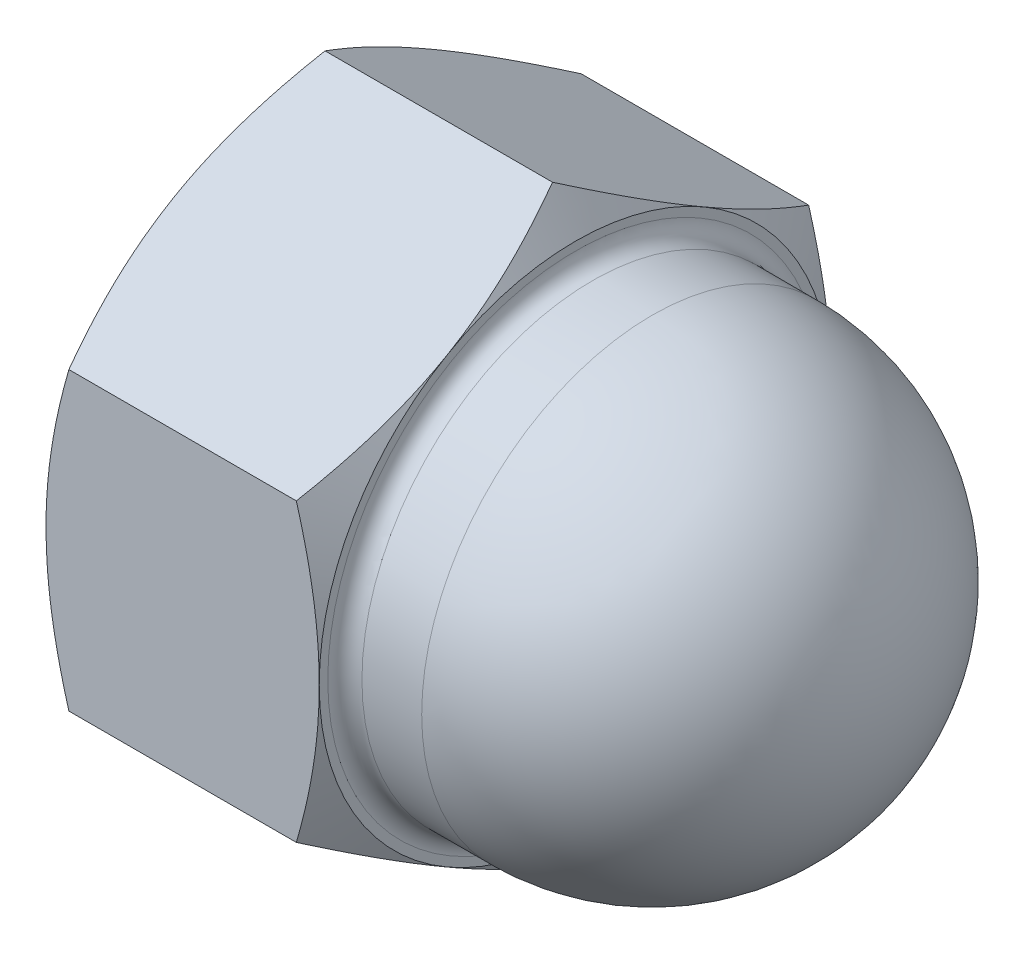
SolidWorks part; units mm, degrees
extrude "BaseNut" add sketch "BaseNutSke" along normal blind 16
sketch "BaseNutSke" plane through (0, 0, 0) normal (1, 0, 0) x (0, 0, -1)
  line L6 (15, 8.6603) -> (15, -8.6603)
  line L7 (-15, 8.6603) -> (-15, -8.6603)
  line L8 (15, 8.6603) -> (0, 17.3205)
  line L9 (0, 17.3205) -> (-15, 8.6603)
  line L10 (-15, -8.6603) -> (0, -17.3205)
  line L11 (0, -17.3205) -> (15, -8.6603)
  dimension "D4" = 60
  dimension "D1" = 120
  dimension "D2" = 15
  dimension "D3" = 15
  dimension "Width_flats" = 30
revolve "DoubleChamfer" cut sketch "Sketch4" angle 360 about L10
sketch "Sketch4" plane through (0, 0, 0) normal (0, 0, 1) x (1, 0, 0)
  line L0 (0, 15) -> (2.7831, 19.8205)
  line L1 (16, 15) -> (13.2169, 19.8205)
  line L2 (2.7831, 19.8205) -> (13.2169, 19.8205)
  line L3 (16, 15) -> (18, 15)
  line L4 (18, 15) -> (18, 30)
  line L5 (18, 30) -> (-2, 30)
  line L6 (0, 15) -> (-2, 15)
  line L7 (-2, 15) -> (-2, 30)
  line L8 (16, 17.3205) -> (16, 8.6603) construction
  line L9 (0, 17.3205) -> (0, 8.6603) construction
  line L10 (0, 0) -> (57.15, 0) construction
  line L11 (16, 17.3205) -> (0, 17.3205) construction
  point P17 (16, 15)
  dimension "D1" = 30
  dimension "D2" = 30
  dimension "D3" = 2
  dimension "D4" = 2
  dimension "D5" = 2.5
  dimension "D6" = 15
  dimension "D7" = 15
revolve "TapDrill" cut sketch "TapDriSke"
sketch "TapDriSke" plane through (0, 0, 0) normal (0, 0, 1) x (1, 0, 0)
  line L0 (0, 0) -> (44.45, 0) construction
  line L1 (0, 8.75) -> (27, 8.75)
  line L2 (0, 12.9904) -> (0, 0) construction
  line L3 (27, 8.75) -> (32.2575, 0)
  line L4 (0, 0) -> (63.5, 0) construction
  line L5 (32.2575, 0) -> (0, 0)
  line L6 (0, 0) -> (0, 8.75)
  line L7 (27, -8.75) -> (32.2575, 0) construction
  line L8 (0, -8.75) -> (27, -8.75) construction
  line L9 (0.5, 6.35) -> (0.5, 3.175) construction
  dimension "Drill_depth" = 27
cosmetic thread "ThreadCosmetic" [suppressed]
revolve "EndChamfer" cut sketch "EndChamferSketch" angle 360 about L4
sketch "EndChamferSketch" plane through (0, 0, 0) normal (0, 0, 1) x (1, 0, 0)
  line L0 (-0.0254, 10) -> (0.0254, 10)
  line L1 (0.0254, 10) -> (0.9882, 8.625)
  line L2 (0.9882, 8.625) -> (-0.0254, 8.625)
  line L3 (-0.0254, 8.625) -> (-0.0254, 10)
  line L4 (0, 0) -> (-15.875, 0) construction
  dimension "D1" = 0.0508
  dimension "D2" = 35
  dimension "D3" = 0.0254
  dimension "ChamferDepth" = 1.375
  dimension "ThreadMajor" = 10
ref_plane "Plane1" through (0, 0, 0) normal (0, 0, 1) x (1, 0, 0)
ref_plane "Plane2" through (0, 0, 0) normal (0, 1, 0) x (1, 0, 0)
ref_plane "Plane3" through (0, 0, 0) normal (1, 0, 0) x (0, 0, -1)
sketch "DomeSke" plane through (0, 0, 0) normal (0, 0, 1) x (1, 0, 0)
  line L0 (0, 0) -> (63.5, 0) construction
  line L1 (0, 8.6603) -> (0, -8.6603) construction
  line L2 (34, 0) -> (0, 0)
  line L3 (0, 13.5) -> (20.5, 13.5)
  line L4 (0, -13.5) -> (22.225, -13.5) construction
  line L5 (0, 13.5) -> (0, 0)
  arc A0 (20.5, 13.5) -> (34, 0) centre (20.5, 0) cw
revolve "Dome" add sketch "DomeSke" angle 360 about L0
sketch "GrvSke" plane through (0, 0, 0) normal (0, 0, 1) x (1, 0, 0)
  line L0 (0, 0) -> (38.1, 0) construction
  line L1 (16, 10.5) -> (16, 7.75)
  line L2 (16, 7.75) -> (22, 7.75)
  line L3 (22, 7.75) -> (22, 10.5)
  line L4 (22, 10.5) -> (16, 10.5)
  line L5 (16, 0) -> (16, 12.9904) construction
  line L6 (27, 8.75) -> (0, 8.75) construction
  dimension "D1" = 1
revolve "Groove" cut sketch "GrvSke" angle 360 about L0
sketch "ThdSchSke" plane through (0, 0, 0) normal (0, 1, 0) x (1, 0, 0)
  line L0 (0.0381, 10) -> (-0.8372, 8.75)
  line L1 (-0.8372, 8.75) -> (-0.8372, 4.375)
  line L2 (-0.8372, 4.375) -> (0.9134, 4.375)
  line L3 (0.9134, 4.375) -> (0.9134, 8.75)
  line L4 (0.9134, 8.75) -> (0.0381, 10)
  line L5 (-38.1, 0) -> (3.175, 0) construction
  line L6 (0, 0) -> (-15.875, 0) construction
  line L7 (0, 0) -> (63.5, 0) construction
  line L9 (2.5381, 0.475) -> (2.5381, -5.875) construction
  dimension "D1" = 0.0381
  dimension "Thread_major" = 20
  dimension "Tap_drill" = 17.5
  dimension "OverCut" = 8.75
revolve "ThreadSchematic" [suppressed] cut sketch "ThdSchSke" angle 360 about L5
pattern_linear "ThdSchPat" [suppressed]
fillet "DomeFillet" radius 1 1 edges at (16, 0, 13.5)
equation "' \"Width_flats@BaseNutSke\" = 30"
equation "' \"Hex_ht@BaseNut\" = 16"
equation "' \"Overall_ht@DomeSke\" = 34"
equation "' \"Dome_rad@DomeSke\" = 13.5"
equation "' \"Thread_min@TapDriSke\" = 17.5"
equation "' \"Drill_clr@TapDriSke\" = 1.0"
equation "' \"Advance@ThdSchSke\" = 2.5"
equation "' \"Thread_nominal@ThreadCosmetic\" = 20"
equation "' \"Radius@DomeFillet\" = 1.0"
equation "' \"Groove_wid@GrvSke\" = 6"
equation "\"Drill_depth@TapDriSke\" = \"Overall_ht@DomeSke\"  - \"Drill_clr@TapDriSke\" - 0.3 * \"Thread_nominal@ThreadCosmetic\""
equation "\"Groove_dia@GrvSke\" = \"Thread_nominal@ThreadCosmetic\" * 1.05"
equation "\"Thread_depth@ThreadCosmetic\" = \"Thread_nominal@ThreadCosmetic\""
equation "\"D2@BaseNutSke\" = \"Width_flats@BaseNutSke\" / 2"
equation "\"D3@BaseNutSke\" = \"Width_flats@BaseNutSke\" / 2"
equation "\"D7@Sketch4\" = \"Width_flats@BaseNutSke\" / 2"
equation "\"D5@Sketch4\" = \"Width_flats@BaseNutSke\" / 12"
equation "\"Thread_major@ThdSchSke\" = \"Thread_nominal@ThreadCosmetic\""
equation "\"Tap_drill@ThdSchSke\" = \"Thread_min@TapDriSke\""
equation "\"OverCut@ThdSchSke\" = \"Tap_drill@ThdSchSke\" * 0.5"
equation "\"Num_threads@ThdSchPat\" = int(  ( \"Hex_ht@BaseNut\" - 0.002 ) / \"Advance@ThdSchSke\" + 0.999 )  + 1"
equation "' \"Num_threads@ThdSchPat\" = int(  ( \"Thread_depth@ThreadCosmetic\" - 0.002 ) / \"Advance@ThdSchSke\" + 0.999 )  + 1"
equation "\"Advance@ThdSchPat\" = ( \"Hex_ht@BaseNut\" - 0.002 ) /  (\"Num_threads@ThdSchPat\" - 1) 'relax it"
equation "' \"Advance@ThdSchPat\" = ( \"Thread_depth@ThreadCosmetic\" - 0.002 ) /  (\"Num_threads@ThdSchPat\" - 1) 'relax it"
equation "\"ThreadMajor@EndChamferSketch\" = \"Thread_nominal@ThreadCosmetic\" * 0.5"
equation "\"ChamferDepth@EndChamferSketch\" = (\"Thread_nominal@ThreadCosmetic\" - \"Thread_min@TapDriSke\") * 0.55"
